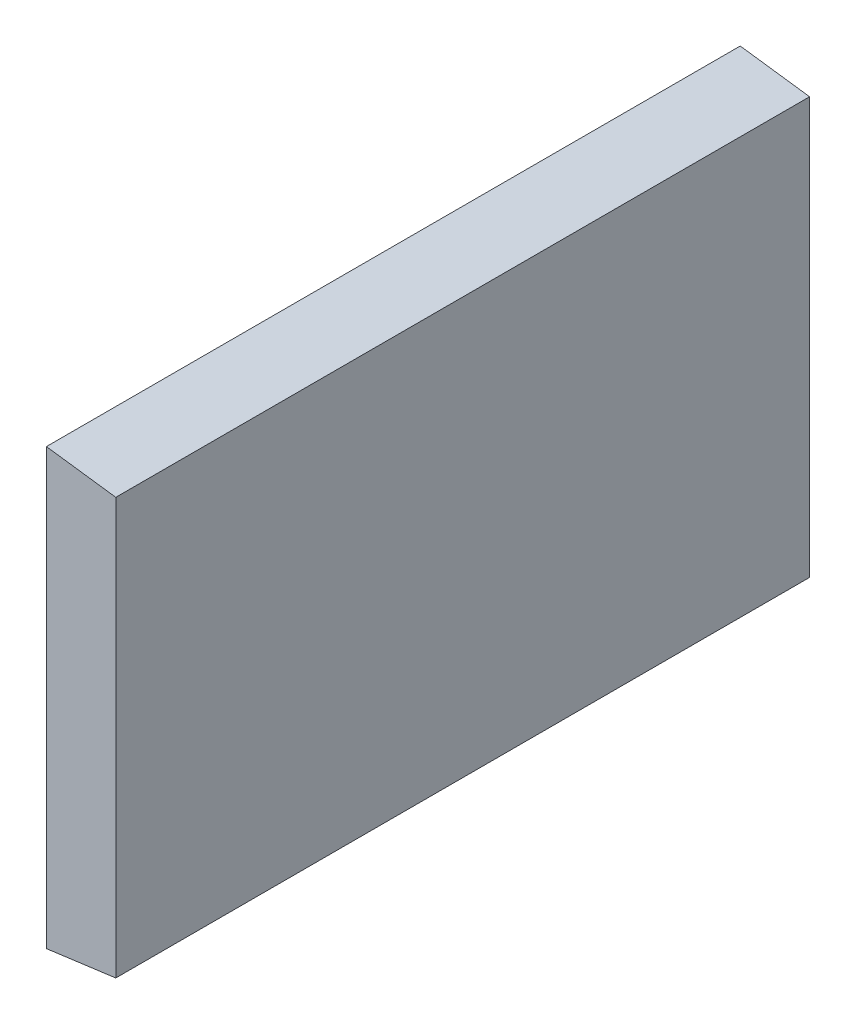
SolidWorks part; units mm, degrees
ref_plane "Ön Düzlem" through (0, 0, 0) normal (0, 0, 1) x (1, 0, 0)
ref_plane "Üst Düzlem" through (0, 0, 0) normal (0, 1, 0) x (1, 0, 0)
ref_plane "Sağ Düzlem" through (0, 0, 0) normal (1, 0, 0) x (0, 0, -1)
sketch "Sketch1" plane through (0, 0, 0) normal (0, 0, 1) x (1, 0, 0)
  line L0 (10, -1.3333) -> (0, 0)
  line L2 (0, 0) -> (0, -62.6667)
  line L4 (0, -62.6667) -> (10, -61.3333)
  line L5 (10, -61.3333) -> (10, -1.3333)
  dimension "D1" = 10
extrude "Boss-Extrude1" add sketch "Sketch1" along normal blind 100
sketch "Sketch2" plane through (10, 0, 0) normal (1, 0, 0) x (0, 0, -1)
  line L0 (0, -61.3333) -> (0, -1.3333) construction
  line L1 (-100, -1.3333) -> (0, -1.3333) construction
  circle A0 centre (-50, -31.3333) radius 20 construction
  point P4 (0, -31.3333)
  point P7 (-50, -1.3333)
  dimension "D1" = 40
